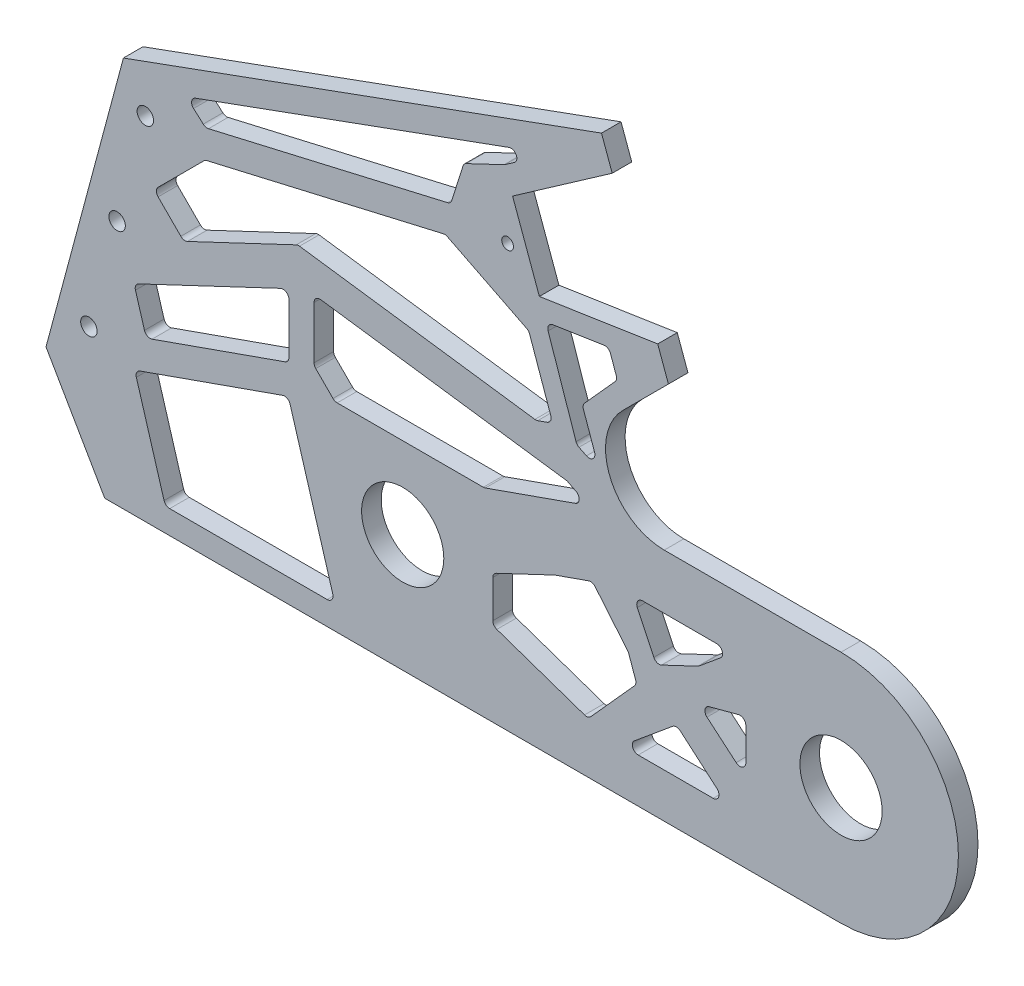
SolidWorks part; units mm, degrees
material "Thornel Mat VMA"
ref_plane "Front Plane" through (0, 0, 0) normal (0, 0, 1) x (1, 0, 0)
ref_plane "Top Plane" through (0, 0, 0) normal (0, 1, 0) x (1, 0, 0)
ref_plane "Right Plane" through (0, 0, 0) normal (1, 0, 0) x (0, 0, -1)
sketch "Sketch1" plane through (0, 0, 0) normal (0, 0, 1) x (1, 0, 0)
  line L0 (-17.6987, 77.2301) -> (94.3013, 77.2301) construction
  line L1 (94.3013, 107.2301) -> (12.9175, 107.2301)
  line L2 (94.3013, 107.2301) -> (94.3013, 47.2301) construction
  line L3 (94.3013, 47.2301) -> (-93.8447, 47.2301)
  line L5 (-93.8447, 47.2301) -> (-108.8447, 73.2109)
  line L6 (-108.8447, 73.2109) -> (-89.0647, 147.031)
  line L7 (-89.0647, 147.031) -> (33.0954, 191.4937)
  line L8 (33.0954, 191.4937) -> (50.1964, 144.509)
  line L9 (50.1964, 144.509) -> (12.9175, 107.2301)
  circle A0 centre (-17.6987, 77.2301) radius 10.5
  circle A1 centre (94.3013, 77.2301) radius 10.5
  arc A2 (94.3013, 47.2301) -> (94.3013, 107.2301) centre (94.3013, 77.2301) ccw
  dimension "D2" = 21
  dimension "D3" = 60
  dimension "D11" = 50
  dimension "D1" = 112
  dimension "D4" = 120
  dimension "D5" = 75
  dimension "D6" = 30
  dimension "D7" = 87
  dimension "D8" = 90
  dimension "D9" = 125
  dimension "D10" = 45
  dimension "D12" = 130
extrude "Boss-Extrude1" add sketch "Sketch1" along normal blind 5
fillet "Fillet1" radius 15 1 edges at (12.9175, 107.2301, 2.5)
sketch "Sketch2" plane through (0, 0, 5) normal (0, 0, 1) x (1, 0, 0)
  line L0 (35.8315, 183.9761) -> (10.3769, 166.198)
  line L1 (50.1964, 144.509) -> (33.0954, 191.4937) construction
  line L2 (10.3769, 166.198) -> (17.2173, 147.4041)
  line L3 (17.2173, 147.4041) -> (47.4602, 152.0266)
  line L4 (35.8315, 183.9761) -> (47.4602, 152.0266)
  line L5 (33.0954, 191.4937) -> (-89.0647, 147.031) construction
  line L6 (9.0987, 155.0909) -> (13.7971, 156.801) construction
  circle A0 centre (9.0987, 155.0909) radius 1.5
  dimension "D7" = 3
  dimension "D1" = 8
  dimension "D2" = 8
  dimension "D3" = 20
  dimension "D4" = 30
  dimension "D5" = 16
  dimension "D6" = 5
extrude "Cut-Extrude1" cut sketch "Sketch2" against normal blind 5
sketch "Sketch4" plane through (0, 0, 5) normal (0, 0, 1) x (1, 0, 0)
  line L0 (-83.4619, 137.031) -> (-97.883, 83.2109) construction
  line L1 (-89.0647, 147.031) -> (-108.8447, 73.2109) construction
  circle A0 centre (-83.4619, 137.031) radius 2.1
  circle A1 centre (-90.6725, 110.121) radius 2.1
  circle A2 centre (-97.883, 83.2109) radius 2.1
  dimension "D1" = 4.2
  dimension "D2" = 8
  dimension "D3" = 10
  dimension "D4" = 10
extrude "Cut-Extrude3" cut sketch "Sketch4" against normal blind 10
sketch "Sketch5" plane through (0, 0, 5) normal (0, 0, 1) x (1, 0, 0)
  line L0 (-48.9186, 116.1326) -> (-85.1915, 98.9849)
  line L1 (-85.9877, 97.1997) -> (-83.6788, 89.4648)
  line L2 (-81.743, 88.4791) -> (-47.779, 100.446)
  line L3 (-46.7775, 101.8608) -> (-46.7775, 114.7765)
  line L4 (-40.3541, 117.2851) -> (-40.3541, 103.9383)
  line L5 (-39.9147, 102.8776) -> (-35.506, 98.4689)
  line L6 (-34.4454, 98.0296) -> (2.9005, 98.0296)
  line L7 (3.399, 98.1148) -> (26.405, 106.2208)
  line L8 (26.5792, 108.9762) -> (24.4981, 110.0205)
  line L9 (24.0294, 110.1658) -> (-38.65, 118.7712)
  line L10 (-74.3921, 114.9226) -> (-80.203, 120.7335)
  line L11 (-80.203, 122.8548) -> (-68.4738, 134.584)
  line L12 (-67.7522, 134.9845) -> (-7.3133, 149.0087)
  line L13 (-6.3015, 148.8882) -> (13.9746, 138.7142)
  line L14 (14.7166, 137.872) -> (20.1407, 122.4778)
  line L15 (19.2244, 120.5646) -> (16.778, 119.7026)
  line L16 (16.0755, 119.6313) -> (-44.068, 127.8885)
  line L17 (-44.9131, 127.7586) -> (-72.6904, 114.6271)
  line L18 (-85.7652, 78.0398) -> (-78.679, 54.3011)
  line L19 (-77.2417, 53.2301) -> (-37.0002, 53.2301)
  line L20 (-35.5629, 55.1592) -> (-46.4788, 91.7273)
  line L21 (-48.4146, 92.713) -> (-84.8263, 79.8836)
  line L22 (-71.1377, 144.8188) -> (-68.6575, 142.606)
  line L23 (-67.3198, 142.2641) -> (-6.2522, 156.4341)
  line L24 (-5.1608, 157.4438) -> (-2.2891, 166.5423)
  line L25 (-1.5025, 167.4456) -> (8.2006, 172.0568)
  line L27 (9.4519, 176.5031) -> (-70.6521, 147.3476)
  line L28 (19.4527, 140.903) -> (26.5975, 119.9597)
  line L29 (27.3444, 119.1033) -> (29.243, 118.1506)
  line L30 (31.3304, 119.9898) -> (28.4804, 128.0786)
  line L31 (28.7794, 129.5796) -> (36.5557, 138.2347)
  line L32 (36.8547, 139.7357) -> (35.3914, 143.8887)
  line L33 (33.75, 144.873) -> (20.6457, 142.8701)
  line L34 (29.8158, 90.7751) -> (21.2915, 87.7716)
  line L35 (21.1489, 87.713) -> (6.1959, 80.6441)
  line L36 (5.337, 79.288) -> (5.337, 69.7174)
  line L37 (6.3484, 68.2992) -> (28.7629, 60.5773)
  line L38 (30.3672, 60.993) -> (41.4975, 73.381)
  line L39 (41.7964, 74.882) -> (40.0589, 79.8133)
  line L40 (39.7988, 80.2723) -> (31.4689, 90.3178)
  line L41 (42.2443, 91.0952) -> (46.4611, 82.1752)
  line L42 (48.4583, 81.4602) -> (57.6936, 85.8261)
  line L43 (58.01, 86.0276) -> (63.5021, 90.5816)
  line L44 (62.5446, 93.2363) -> (43.6004, 93.2363)
  line L45 (51.2686, 69.3073) -> (41.512, 61.217)
  line L46 (42.4695, 58.5623) -> (61.6224, 58.5623)
  line L47 (62.6011, 61.199) -> (53.2047, 69.2893)
  line L48 (67.4986, 69.4018) -> (60.0466, 75.7313)
  line L49 (60.6304, 78.3237) -> (68.0824, 80.3149)
  line L50 (69.9696, 78.8657) -> (69.9696, 70.5451)
  line L51 (33.0954, 191.4937) -> (-89.0647, 147.031) construction
  line L52 (-93.8447, 47.2301) -> (94.3013, 47.2301) construction
  line L53 (8.4157, 172.1819) -> (10.8238, 173.8638)
  line L54 (35.8315, 183.9761) -> (10.3769, 166.198) construction
  line L55 (17.2173, 147.4041) -> (47.4602, 152.0266) construction
  arc A0 (-37.0002, 53.2301) -> (-35.5629, 55.1592) centre (-37.0002, 54.7301) ccw
  arc A1 (-78.679, 54.3011) -> (-77.2417, 53.2301) centre (-77.2417, 54.7301) ccw
  arc A2 (-85.7652, 78.0398) -> (-84.8263, 79.8836) centre (-84.3278, 78.4688) cw
  arc A3 (-46.4788, 91.7273) -> (-48.4146, 92.713) centre (-47.9161, 91.2982) ccw
  arc A4 (61.6224, 58.5623) -> (62.6011, 61.199) centre (61.6224, 60.0623) ccw
  arc A5 (41.512, 61.217) -> (42.4695, 58.5623) centre (42.4695, 60.0623) ccw
  arc A6 (51.2686, 69.3073) -> (53.2047, 69.2893) centre (52.226, 68.1526) cw
  arc A7 (67.4986, 69.4018) -> (69.9696, 70.5451) centre (68.4696, 70.5451) ccw
  arc A8 (60.0466, 75.7313) -> (60.6304, 78.3237) centre (61.0176, 76.8745) cw
  arc A9 (68.0824, 80.3149) -> (69.9696, 78.8657) centre (68.4696, 78.8657) cw
  arc A10 (63.5021, 90.5816) -> (62.5446, 93.2363) centre (62.5446, 91.7363) ccw
  arc A11 (57.6936, 85.8261) -> (58.01, 86.0276) centre (57.0525, 87.1822) ccw
  arc A12 (46.4611, 82.1752) -> (48.4583, 81.4602) centre (47.8172, 82.8163) ccw
  arc A13 (42.2443, 91.0952) -> (43.6004, 93.2363) centre (43.6004, 91.7363) cw
  arc A14 (40.0589, 79.8133) -> (39.7988, 80.2723) centre (38.6442, 79.3148) ccw
  arc A15 (41.4975, 73.381) -> (41.7964, 74.882) centre (40.3817, 74.3835) ccw
  arc A16 (28.7629, 60.5773) -> (30.3672, 60.993) centre (29.2514, 61.9955) ccw
  arc A17 (5.337, 69.7174) -> (6.3484, 68.2992) centre (6.837, 69.7174) ccw
  arc A18 (6.1959, 80.6441) -> (5.337, 79.288) centre (6.837, 79.288) ccw
  arc A19 (21.2915, 87.7716) -> (21.1489, 87.713) centre (21.7899, 86.3569) ccw
  arc A20 (29.8158, 90.7751) -> (31.4689, 90.3178) centre (30.3143, 89.3603) cw
  arc A21 (24.4981, 110.0205) -> (24.0294, 110.1658) centre (23.8254, 108.6798) ccw
  arc A22 (26.405, 106.2208) -> (26.5792, 108.9762) centre (25.9065, 107.6355) ccw
  arc A23 (2.9005, 98.0296) -> (3.399, 98.1148) centre (2.9005, 99.5296) ccw
  arc A24 (-35.506, 98.4689) -> (-34.4454, 98.0296) centre (-34.4454, 99.5296) ccw
  arc A25 (-40.3541, 103.9383) -> (-39.9147, 102.8776) centre (-38.8541, 103.9383) ccw
  arc A26 (-40.3541, 117.2851) -> (-38.65, 118.7712) centre (-38.8541, 117.2851) cw
  arc A27 (-48.9186, 116.1326) -> (-46.7775, 114.7765) centre (-48.2775, 114.7765) cw
  arc A28 (-47.779, 100.446) -> (-46.7775, 101.8608) centre (-48.2775, 101.8608) ccw
  arc A29 (-83.6788, 89.4648) -> (-81.743, 88.4791) centre (-82.2415, 89.8938) ccw
  arc A30 (-85.1915, 98.9849) -> (-85.9877, 97.1997) centre (-84.5504, 97.6288) ccw
  arc A31 (36.5557, 138.2347) -> (36.8547, 139.7357) centre (35.44, 139.2372) ccw
  arc A32 (35.3914, 143.8887) -> (33.75, 144.873) centre (33.9767, 143.3902) ccw
  arc A33 (19.4527, 140.903) -> (20.6457, 142.8701) centre (20.8723, 141.3873) cw
  arc A34 (28.4804, 128.0786) -> (28.7794, 129.5796) centre (29.8952, 128.5771) cw
  arc A35 (29.243, 118.1506) -> (31.3304, 119.9898) centre (29.9157, 119.4913) ccw
  arc A36 (26.5975, 119.9597) -> (27.3444, 119.1033) centre (28.0171, 120.444) ccw
  arc A37 (16.778, 119.7026) -> (16.0755, 119.6313) centre (16.2796, 121.1174) cw
  arc A38 (20.1407, 122.4778) -> (19.2244, 120.5646) centre (18.7259, 121.9793) cw
  arc A39 (13.9746, 138.7142) -> (14.7166, 137.872) centre (13.3019, 137.3736) cw
  arc A40 (-7.3133, 149.0087) -> (-6.3015, 148.8882) centre (-6.9742, 147.5475) cw
  arc A41 (-44.068, 127.8885) -> (-44.9131, 127.7586) centre (-44.2721, 126.4025) ccw
  arc A42 (-74.3921, 114.9226) -> (-72.6904, 114.6271) centre (-73.3315, 115.9832) ccw
  arc A43 (-80.203, 120.7335) -> (-80.203, 122.8548) centre (-79.1423, 121.7941) cw
  arc A44 (-68.4738, 134.584) -> (-67.7522, 134.9845) centre (-67.4131, 133.5233) cw
  arc A45 (10.8238, 173.8638) -> (9.4519, 176.5031) centre (9.9649, 175.0935) ccw
  arc A46 (8.2006, 172.0568) -> (8.4157, 172.1819) centre (7.5568, 173.4116) ccw
  arc A47 (-2.2891, 166.5423) -> (-1.5025, 167.4456) centre (-0.8587, 166.0908) cw
  arc A48 (-6.2522, 156.4341) -> (-5.1608, 157.4438) centre (-6.5913, 157.8953) ccw
  arc A49 (-68.6575, 142.606) -> (-67.3198, 142.2641) centre (-67.6589, 143.7253) ccw
  arc A50 (-71.1377, 144.8188) -> (-70.6521, 147.3476) centre (-70.1391, 145.938) cw
  point P55 (-73.0101, 146.6247)
  point P56 (-63.451, 142.3551)
  point P57 (-5.8274, 149.6914)
  point P58 (-8.7619, 155.9607)
  point P59 (-2.0925, 167.1653)
  point P60 (-5.3668, 156.6276)
  point P61 (-68.1703, 142.0883)
  point P62 (8.7119, 171.5671)
  point P65 (12.5802, 137.0196)
  point P66 (-44.5099, 127.9492)
  point P67 (0, 0)
  point P68 (-46.7775, 117.1448)
  point P71 (24.2758, 119.5819)
  point P72 (26.7263, 119.5819)
  point P73 (32.5659, 116.4833)
  point P74 (41.2321, 93.2363)
  point P75 (65.9706, 93.2363)
  point P76 (57.8645, 85.9069)
  point P77 (57.8645, 77.5846)
  point P78 (69.9696, 80.8191)
  dimension "D4" = 1.5
  dimension "D1" = 6
  dimension "D2" = 6
  dimension "D3" = 5
extrude "Cut-Extrude4" cut sketch "Sketch5" against normal blind 10
